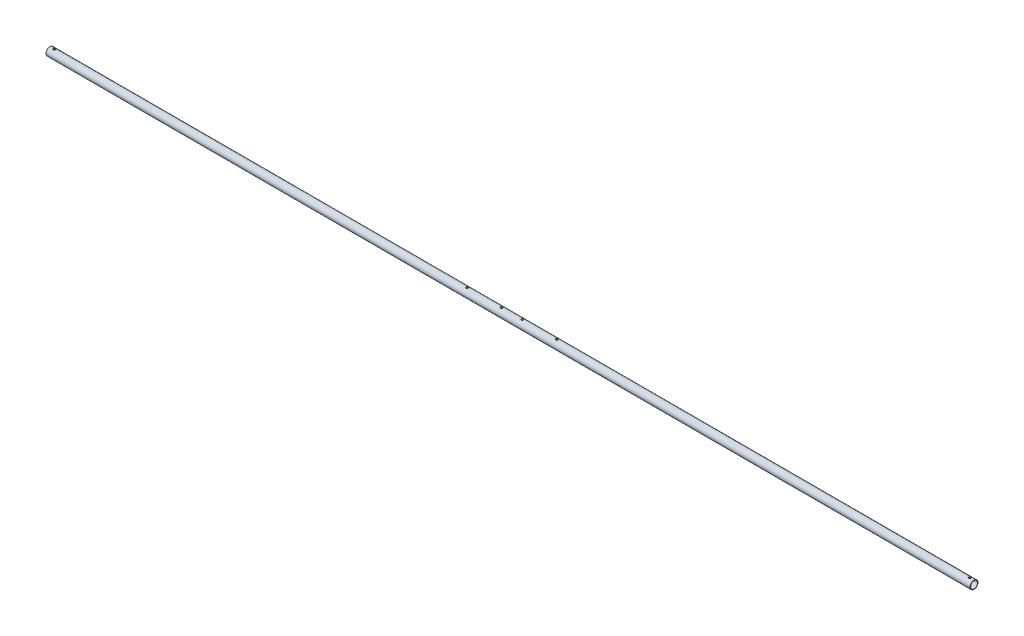
SolidWorks part; units mm, degrees
other "DetailItem1"
material "Galvanized Steel"
ref_plane "Front Plane" through (0, 0, 0) normal (0, 0, 1) x (1, 0, 0)
ref_plane "Top Plane" through (0, 0, 0) normal (0, 1, 0) x (1, 0, 0)
ref_plane "Right Plane" through (0, 0, 0) normal (1, 0, 0) x (0, 0, -1)
sketch "Sketch3" plane through (0, 0, 0) normal (1, 0, 0) x (0, 0, -1)
  circle A0 centre (0, 0) radius 10.4648
  circle A1 centre (0, 0) radius 11.7094
  dimension "D1" = 20.9296
  dimension "D2" = 23.4188
extrude "Boss-Extrude1" add sketch "Sketch3" along normal blind 2724.912
sketch "Sketch4" plane through (0, 0, 0) normal (0, 1, 0) x (1, 0, 0)
  line L0 (0, 11.7094) -> (0, -11.7094) construction
  circle A0 centre (1331.976, 0) radius 3.175
  circle A1 centre (1392.936, 0) radius 3.175
  circle A2 centre (1494.6376, 0) radius 3.175
  circle A3 centre (1230.2744, 0) radius 3.175
  point P0 (1362.456, 0)
  point P1 (1392.936, 0)
  point P3 (1331.976, 0)
  dimension "D4" = 6.35
  dimension "D5" = 6.35
  dimension "D6" = 132.1816
  dimension "D1" = 1362.456
  dimension "D2" = 30.48
  dimension "D3" = 30.48
  dimension "D7" = 132.1816
extrude "Cut-Extrude1" cut sketch "Sketch4" against normal through all and the other way through all
sketch "Sketch5" plane through (0, 0, 0) normal (0, 1, 0) x (1, 0, 0)
  line L0 (2724.912, -11.7094) -> (2724.912, 11.7094) construction
  circle A0 centre (12.7, 0) radius 3.175
  circle A1 centre (2712.212, 0) radius 3.175
  point P0 (12.7, 0)
  point P4 (2712.212, 0)
  dimension "D2" = 6.35
  dimension "D4" = 6.35
  dimension "D1" = 12.7
  dimension "D3" = 12.7
extrude "Cut-Extrude2" cut sketch "Sketch5" against normal through all and the other way through all
